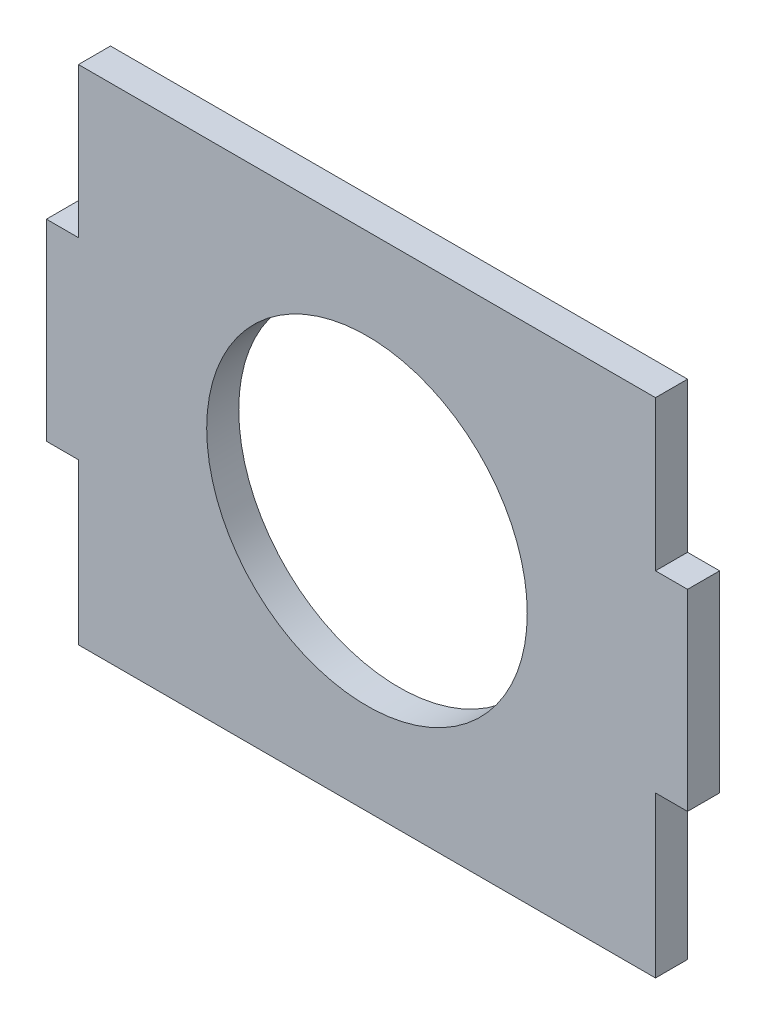
SolidWorks part; units mm, degrees
ref_plane "Front Plane" through (0, 0, 0) normal (0, 0, 1) x (1, 0, 0)
ref_plane "Top Plane" through (0, 0, 0) normal (0, 1, 0) x (1, 0, 0)
ref_plane "Right Plane" through (0, 0, 0) normal (1, 0, 0) x (0, 0, -1)
sketch "Sketch1" plane through (0, 0, 0) normal (0, 0, 1) x (1, 0, 0)
  line L1 (-3.175, 56.1265) -> (-60.325, 56.1265)
  line L2 (0, 41.275) -> (0, 22.225)
  line L3 (-3.175, 6.35) -> (-60.325, 6.35)
  line L4 (-63.5, 41.275) -> (-63.5, 22.225)
  line L6 (-60.325, 41.275) -> (-63.5, 41.275)
  line L7 (-60.325, 41.275) -> (-60.325, 56.1265)
  line L12 (-63.5, 22.225) -> (-60.325, 22.225)
  line L13 (-60.325, 6.35) -> (-60.325, 22.225)
  line L14 (-3.175, 22.225) -> (0, 22.225)
  line L15 (-3.175, 22.225) -> (-3.175, 6.35)
  line L18 (-3.175, 41.275) -> (0, 41.275)
  line L19 (-3.175, 41.275) -> (-3.175, 56.1265)
  circle A0 centre (-31.75, 31.2737) radius 15.875
  dimension "D1" = 31.75
extrude "Boss-Extrude1" add sketch "Sketch1" along normal blind 3.175 contours L1 L7 L6 L4 L12 L13 L3 L15 L14 L2 L18 L19
